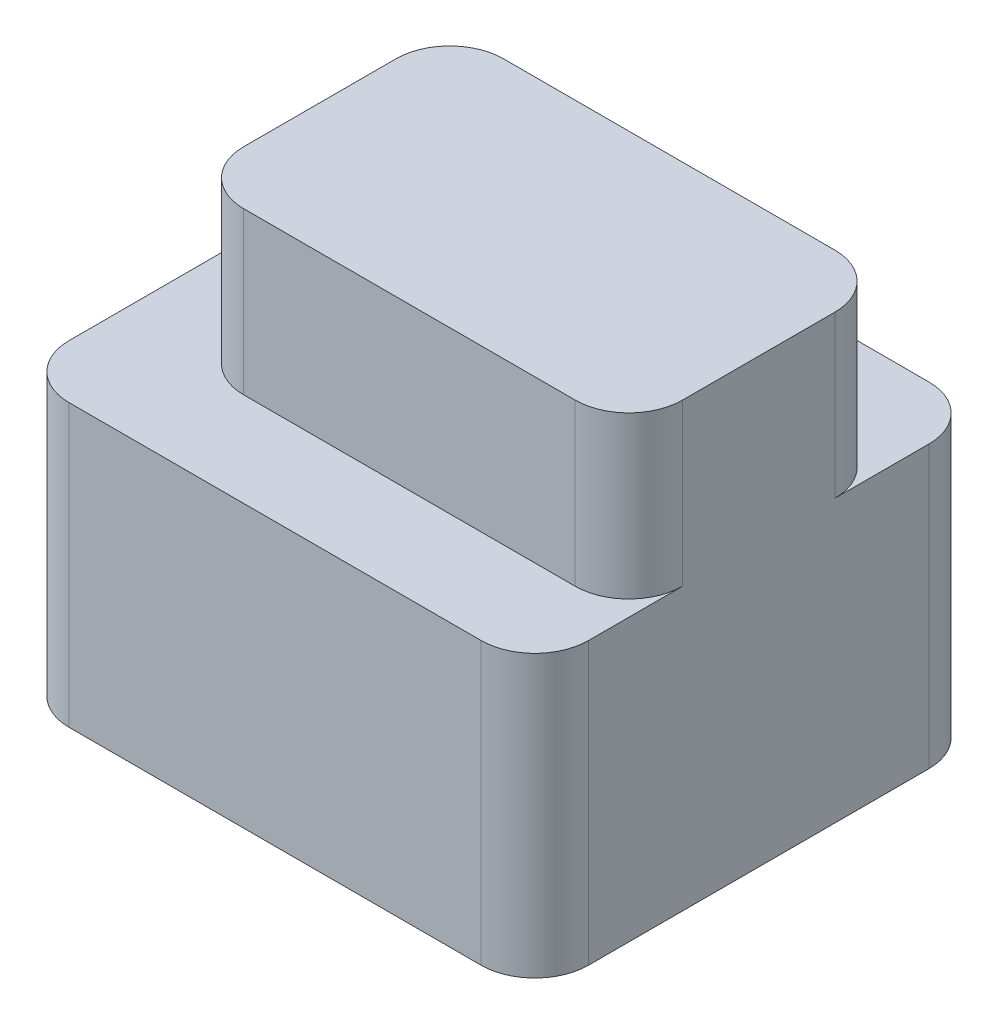
SolidWorks part; units mm, degrees
ref_plane "Front Plane" through (0, 0, 0) normal (0, 0, 1) x (1, 0, 0)
ref_plane "Top Plane" through (0, 0, 0) normal (0, 1, 0) x (1, 0, 0)
ref_plane "Right Plane" through (0, 0, 0) normal (1, 0, 0) x (0, 0, -1)
ref_plane "Plane1" through (0, 0, 0) normal (0, -1, 0) x (1, 0, 0)
sketch "Sketch1" plane through (0, 0, 0) normal (0, -1, 0) x (1, 0, 0)
  line L0 (0, 110) -> (5.8, 110)
  line L1 (5.8, 110) -> (5.8, 115)
  line L2 (5.8, 115) -> (0, 115)
  line L3 (0, 115) -> (0, 110)
extrude "Boss-Extrude1" add sketch "Sketch1" against normal blind 0.8
sketch "Sketch2" plane through (0, 0.8, 0) normal (0, 1, 0) x (-1, 0, 0)
  line L0 (-5.8, 113.95) -> (-0.9, 113.95)
  line L1 (-0.9, 113.95) -> (-0.9, 111.05)
  line L2 (-0.9, 111.05) -> (-5.8, 111.05)
  line L3 (-5.8, 111.05) -> (-5.8, 113.95)
extrude "Boss-Extrude2" add sketch "Sketch2" along normal blind 1.8
fillet "Fillet1" radius 0.6 8 edges at (5.8, 0.4, 110) (0, 0.4, 115) (5.8, 0.4, 115) (0.9, 1.7, 111.05) (0, 0.4, 110) (0.9, 1.7, 113.95) (5.8, 1.7, 111.05) (5.8, 1.7, 113.95)
sketch "Sketch3" plane through (0, 0, 0) normal (0, -1, 0) x (1, 0, 0)
  line L8 (0.6, 110) -> (5.2, 110)
  line L9 (5.8, 110.6) -> (5.8, 114.4)
  line L10 (5.2, 115) -> (0.6, 115)
  line L11 (0, 114.4) -> (0, 110.6)
  line L12 (0.6, 110) -> (5.2, 110)
  line L13 (5.8, 110.6) -> (5.8, 114.4)
  line L14 (5.2, 115) -> (0.6, 115)
  line L15 (0, 114.4) -> (0, 110.6)
  arc A8 (5.2, 110) -> (5.8, 110.6) centre (5.2, 110.6) ccw
  arc A9 (5.8, 114.4) -> (5.2, 115) centre (5.2, 114.4) ccw
  arc A10 (0.6, 115) -> (0, 114.4) centre (0.6, 114.4) ccw
  arc A11 (0, 110.6) -> (0.6, 110) centre (0.6, 110.6) ccw
  arc A12 (5.2, 110) -> (5.8, 110.6) centre (5.2, 110.6) ccw
  arc A13 (5.8, 114.4) -> (5.2, 115) centre (5.2, 114.4) ccw
  arc A14 (0.6, 115) -> (0, 114.4) centre (0.6, 114.4) ccw
  arc A15 (0, 110.6) -> (0.6, 110) centre (0.6, 110.6) ccw
  dimension "D1" = 0
extrude "Boss-Extrude3" add sketch "Sketch3" along normal blind 2.34
